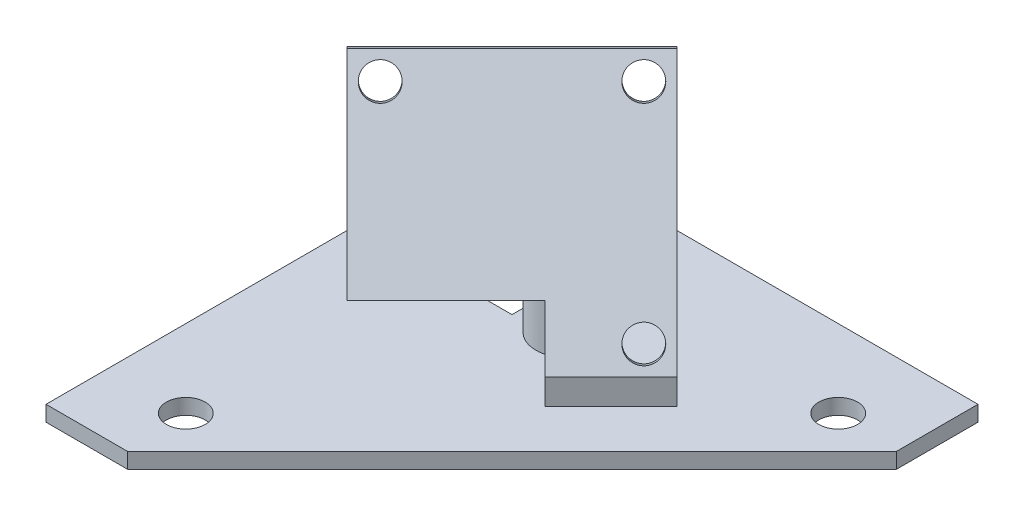
SolidWorks part; units mm, degrees
ref_plane "Front" through (0, 0, 0) normal (0, 0, 1) x (1, 0, 0)
ref_plane "Top" through (0, 0, 0) normal (0, 1, 0) x (1, 0, 0)
ref_plane "Right" through (0, 0, 0) normal (1, 0, 0) x (0, 0, -1)
sketch "草图1" plane through (0, 0, 0) normal (0, 1, 0) x (1, 0, 0)
  line L0 (87.1745, 16.672) -> (1.4976, -69.0049)
  line L1 (0, 0) -> (60, 0)
  line L2 (0, 0) -> (0, -60)
  line L3 (0, -60) -> (60, -60)
  line L4 (60, 0) -> (60, -60)
  line L5 (0, 0) -> (20, 0)
  line L6 (0, 0) -> (0, -20)
  line L7 (0, -20) -> (20, -20)
  line L8 (20, 0) -> (20, -20)
  circle A0 centre (10, -52) radius 2.5
  circle A1 centre (52, -10) radius 2.5
  dimension "D5" = 5
  dimension "D8" = 5
  dimension "D1" = 60
  dimension "D2" = 60
  dimension "D3" = 20
  dimension "D4" = 20
  dimension "D6" = 10
  dimension "D7" = 8
  dimension "D9" = 10
  dimension "D10" = 8
  dimension "D11" = 35
extrude "凸台-拉伸1" add sketch "草图1" along normal blind 2 contours L1 L8 L7 L2 L3 L4
ref_plane "基准面1" through (23.1124, 18.8712, 23.1124) normal (0.6124, 0.5, 0.6124) x (-0.7071, 0, 0.7071)
sketch "草图2" plane through (23.1124, 18.8712, 23.1124) normal (0.6124, 0.5, 0.6124) x (-0.7071, 0, 0.7071)
  line L0 (20.7547, -10.214) -> (-21.3736, -10.214) construction
  line L1 (-15, 16.786) -> (15, 16.786)
  line L2 (-15, 16.786) -> (-15, -13.214)
  line L3 (-15, -13.214) -> (15, -13.214)
  line L4 (15, 16.786) -> (15, -13.214)
  line L5 (-15, 16.786) -> (15, -13.214) construction
  line L6 (-15, -13.214) -> (15, 16.786) construction
  line L7 (0, -2.8326) -> (0, 36.0846) construction
  line L8 (27.4605, 1.786) -> (-33.4746, 1.786) construction
  line L10 (15, 16.786) -> (-3, 16.786)
  line L11 (15, 16.786) -> (15, 9.786)
  line L12 (15, 9.786) -> (-3, 9.786)
  line L13 (-3, 16.786) -> (-3, 9.786)
  circle A0 centre (12, -10.214) radius 2
  circle A1 centre (-12, -10.214) radius 2
  circle A2 centre (-12, 13.786) radius 2
  circle A3 centre (12, 13.786) radius 2
  point P0 (0, 1.786)
  dimension "D4" = 4
  dimension "D1" = 30
  dimension "D2" = 30
  dimension "D3" = 12
  dimension "D5" = 12
  dimension "D6" = 7
  dimension "D7" = 18
extrude "凸台-拉伸3" add sketch "草图2" along normal blind 2 separate body contours L13 L1 L2 L3 L4 L12 A2 A0 A1
sketch "草图4" plane through (0, 2, 0) normal (0, 1, 0) x (1, 0, 0)
  line L12 (28.6936, -38.5931) -> (31.1685, -41.0679)
  line L13 (15.9657, -51.321) -> (28.6936, -38.5931)
  line L14 (-6.3082, -29.0471) -> (15.9657, -51.321)
  line L15 (29.0471, 6.3082) -> (-6.3082, -29.0471)
  line L16 (53.7959, -18.4405) -> (29.0471, 6.3082)
  line L17 (31.1685, -41.0679) -> (53.7959, -18.4405)
  line L18 (28.6936, -38.5931) -> (31.1685, -41.0679)
  line L19 (15.9657, -51.321) -> (28.6936, -38.5931)
  line L20 (-6.3082, -29.0471) -> (15.9657, -51.321)
  line L21 (29.0471, 6.3082) -> (-6.3082, -29.0471)
  line L22 (53.7959, -18.4405) -> (29.0471, 6.3082)
  line L23 (31.1685, -41.0679) -> (53.7959, -18.4405)
  circle A0 centre (25.5116, -18.4405) radius 4
  dimension "D2" = 8
  dimension "D3" = 15
  dimension "D4" = 20
  dimension "D1" = 10
extrude "凸台-拉伸4" add sketch "草图4" along normal up to surface (14.7556 mm away) contours A0
sketch "草图5" plane through (0, 2, 0) normal (0, 1, 0) x (1, 0, 0)
  line L4 (39.6537, -18.4405) -> (31.1685, -26.9258)
  line L5 (40.8785, -19.6653) -> (39.6537, -18.4405)
  line L6 (32.3932, -28.1506) -> (40.8785, -19.6653)
  line L7 (60, 0) -> (20, 0)
  line L8 (20, 0) -> (20, -20)
  line L9 (20, -20) -> (0, -20)
  line L10 (0, -20) -> (0, -60)
  line L11 (0, -60) -> (10.5025, -60)
  line L12 (10.5025, -60) -> (60, -10.5025)
  line L13 (60, -10.5025) -> (60, 0)
  line L14 (60, 0) -> (20, 0)
  line L15 (20, 0) -> (20, -20)
  line L16 (20, -20) -> (0, -20)
  line L17 (0, -20) -> (0, -60)
  line L18 (0, -60) -> (10.5025, -60)
  line L19 (10.5025, -60) -> (60, -10.5025)
  line L20 (60, -10.5025) -> (60, 0)
  line L21 (31.1685, -26.9258) -> (32.3932, -28.1506)
  line L22 (39.6537, -18.4405) -> (31.1685, -26.9258)
  line L23 (40.8785, -19.6653) -> (39.6537, -18.4405)
  line L24 (32.3932, -28.1506) -> (40.8785, -19.6653)
  line L25 (31.1685, -26.9258) -> (32.3932, -28.1506)
  dimension "D1" = 0
  dimension "D2" = 0
extrude "凸台-拉伸5" add sketch "草图5" along normal up to next contours L22 L25 L24 L23
